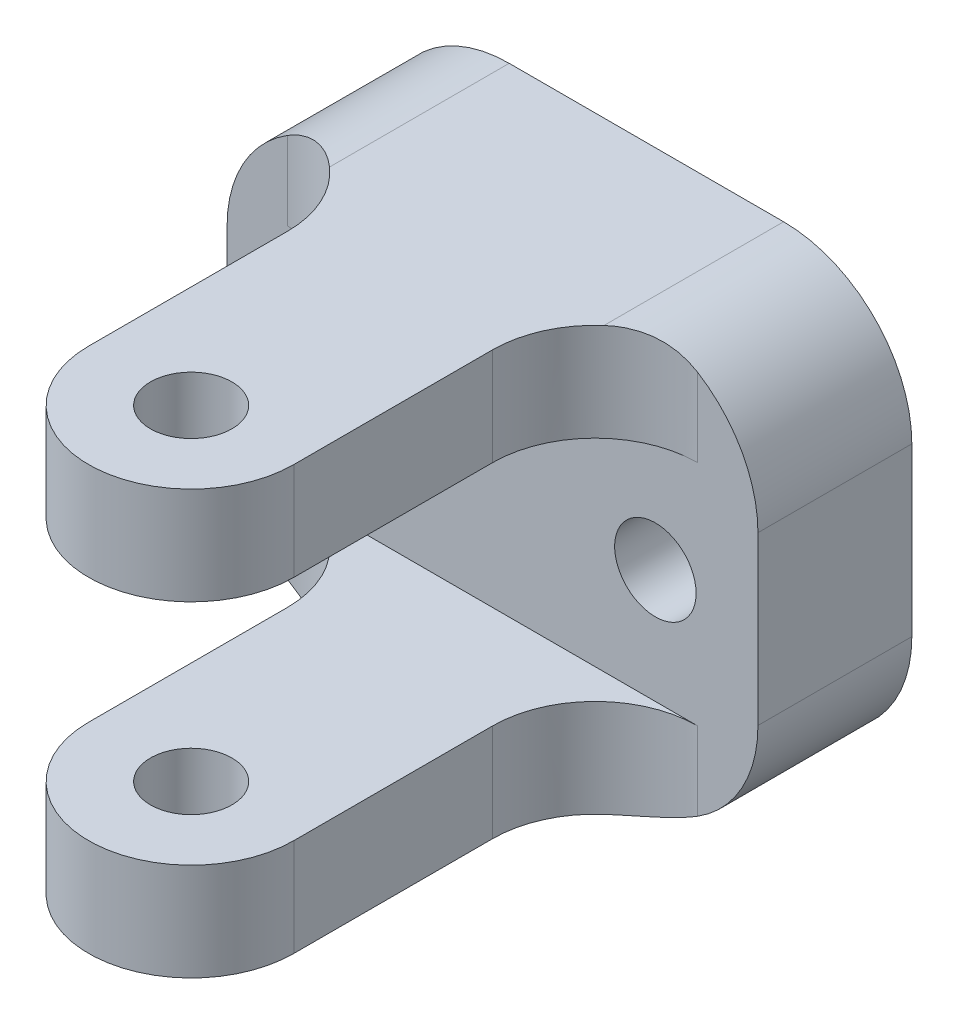
SolidWorks part; units mm, degrees
material "7075-T6 (SN)"
ref_plane "Front Plane" through (0, 0, 0) normal (0, 0, 1) x (1, 0, 0)
ref_plane "Top Plane" through (0, 0, 0) normal (0, 1, 0) x (1, 0, 0)
ref_plane "Right Plane" through (0, 0, 0) normal (1, 0, 0) x (0, 0, -1)
sketch "Sketch1" plane through (0, 0, 0) normal (0, 0, 1) x (1, 0, 0)
  line L0 (12.7, 0) -> (-12.7, 0) construction
  line L1 (-20.7, -16.51) -> (20.7, -16.51)
  line L2 (-20.7, -16.51) -> (-20.7, 16.51)
  line L3 (-20.7, 16.51) -> (20.7, 16.51)
  line L4 (20.7, -16.51) -> (20.7, 16.51)
  line L5 (-20.7, -16.51) -> (20.7, 16.51) construction
  line L6 (-20.7, 16.51) -> (20.7, -16.51) construction
  circle A0 centre (12.7, 0) radius 3.175
  circle A1 centre (-12.7, 0) radius 3.175
  point P0 (0, 0)
  dimension "D1" = 6.35
  dimension "D2" = 25.4
  dimension "D3" = 8
  dimension "D4" = 16.51
extrude "Boss-Extrude1" add sketch "Sketch1" along normal blind 12 contours L3 L4 L1 L2
sketch "Sketch2" plane through (0, 0, 12) normal (0, 0, 1) x (1, 0, 0)
  line L0 (-12.7, 0) -> (12.7, 0) construction
  line L2 (-20.7, 8.89) -> (20.7, 8.89)
  line L3 (-20.7, 8.89) -> (-20.7, 16.51)
  line L4 (-20.7, 16.51) -> (20.7, 16.51)
  line L5 (20.7, 8.89) -> (20.7, 16.51)
  line L6 (-20.7, 8.89) -> (20.7, 16.51) construction
  line L7 (-20.7, 16.51) -> (20.7, 8.89) construction
  line L8 (-20.7, 16.51) -> (-20.7, -16.51) construction
  line L9 (20.7, -8.89) -> (20.7, -16.51)
  line L10 (-20.7, -8.89) -> (-20.7, -16.51)
  line L11 (-20.7, -16.51) -> (20.7, -8.89) construction
  line L12 (-20.7, -8.89) -> (20.7, -16.51) construction
  line L13 (-20.7, -8.89) -> (20.7, -8.89)
  line L14 (-20.7, -16.51) -> (20.7, -16.51)
  circle A0 centre (-12.7, 0) radius 3.175 construction
  circle A1 centre (12.7, 0) radius 3.175 construction
  point P6 (0, 12.7)
  point P21 (0, -12.7)
  dimension "D1" = 17.78
extrude "Boss-Extrude2" add sketch "Sketch2" along normal blind 53
sketch "Sketch3" plane through (0, 0, 0) normal (0, 1, 0) x (1, 0, 0)
  point P0 (0, -35.5)
  dimension "D1" = 35.5
ref_point "UBJ Point"
sketch "Sketch4" plane through (0, 0, 0) normal (0, 1, 0) x (1, 0, 0)
  circle A0 centre (0, -35.5) radius 3.175
  dimension "D1" = 6.35
extrude "Cut-Extrude1" cut sketch "Sketch4" against normal up to surface and the other way up to surface up to face at (0, -16.51, 32.5) other way up to face at (0, 16.51, 32.5)
sketch "Sketch5" plane through (0, 0, 0) normal (0, 1, 0) x (1, 0, 0)
  line L0 (20.7, -12) -> (8.3595, -39.2814)
  line L1 (-8.3595, -39.2814) -> (-20.7, -12)
  line L4 (20.7, 0) -> (-20.7, 0)
  line L5 (-20.7, 0) -> (-20.7, -65)
  line L6 (-20.7, -65) -> (20.7, -65)
  line L7 (20.7, -65) -> (20.7, 0)
  line L9 (-20.7, -12) -> (-20.7, -65)
  line L10 (-20.7, -65) -> (20.7, -65)
  line L11 (20.7, -65) -> (20.7, -12)
  line L12 (20.7, -12) -> (-20.7, -12)
  line L13 (20.7, -65) -> (20.7, -12)
  line L14 (-20.7, -65) -> (20.7, -65)
  line L15 (-20.7, -12) -> (-20.7, -65)
  line L17 (20.7, -65) -> (20.7, -12)
  line L18 (-20.7, -65) -> (20.7, -65)
  line L19 (-20.7, -12) -> (-20.7, -65)
  arc A0 (-8.3595, -39.2814) -> (8.3595, -39.2814) centre (0, -35.5) ccw
  circle A1 centre (0, -35.5) radius 3.175 construction
  circle A2 centre (0, -35.5) radius 3.175 construction
  dimension "D3" = 6
  dimension "D1" = 0
  dimension "D2" = 0
extrude "Cut-Extrude2" [suppressed] cut sketch "Sketch5" against normal up to surface and the other way up to surface contours A0 L1 L9 L10 L11 L0
sketch "Sketch6" plane through (0, 0, 0) normal (0, 1, 0) x (1, 0, 0)
  line L0 (-8, -35.5) -> (-8, -20)
  line L1 (8, -35.5) -> (8, -20)
  line L2 (-16, -12) -> (-20.7, -12)
  line L4 (20.7, -12) -> (-20.7, -12)
  line L5 (-20.7, -12) -> (-20.7, -65)
  line L6 (-20.7, -65) -> (20.7, -65)
  line L7 (20.7, -65) -> (20.7, -12)
  line L8 (20.7, -12) -> (16, -12)
  line L9 (-20.7, -12) -> (-20.7, -65)
  line L10 (-20.7, -65) -> (20.7, -65)
  line L11 (20.7, -65) -> (20.7, -12)
  arc A0 (-8, -35.5) -> (8, -35.5) centre (0, -35.5) ccw
  circle A1 centre (0, -35.5) radius 3.175 construction
  arc A2 (-8, -20) -> (-16, -12) centre (-16, -20) ccw
  arc A3 (8, -20) -> (16, -12) centre (16, -20) cw
  dimension "D2" = 8
  dimension "D3" = 8
  dimension "D1" = 0
extrude "Cut-Extrude3" cut sketch "Sketch6" against normal up to surface and the other way up to surface up to face at (0, -16.51, 38.675) other way up to face at (0, 16.51, 32.325)
fillet "Fillet1" radius 10 4 edges at (-20.7, -16.51, 6) (-20.7, 16.51, 6) (20.7, -16.51, 6) (20.7, 16.51, 6)
